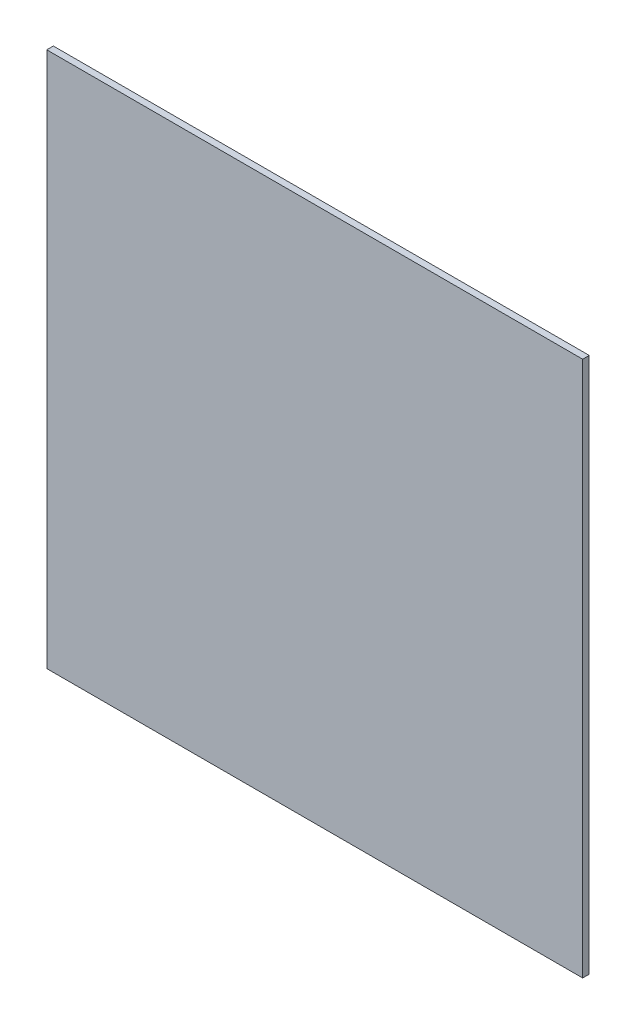
SolidWorks part; units mm, degrees
material "Maple"
ref_plane "Front Plane" through (0, 0, 0) normal (0, 0, 1) x (1, 0, 0)
ref_plane "Top Plane" through (0, 0, 0) normal (0, 1, 0) x (1, 0, 0)
ref_plane "Right Plane" through (0, 0, 0) normal (1, 0, 0) x (0, 0, -1)
sketch "Sketch1" plane through (0, 0, 0) normal (0, 0, 1) x (1, 0, 0)
  line L1 (0, 0) -> (711.2, 0)
  line L2 (0, 0) -> (0, 711.2)
  line L3 (0, 711.2) -> (711.2, 711.2)
  line L4 (711.2, 0) -> (711.2, 711.2)
  dimension "D1" = 711.2
  dimension "D2" = 711.2
extrude "Boss-Extrude1" add sketch "Sketch1" along normal blind 8.7312
